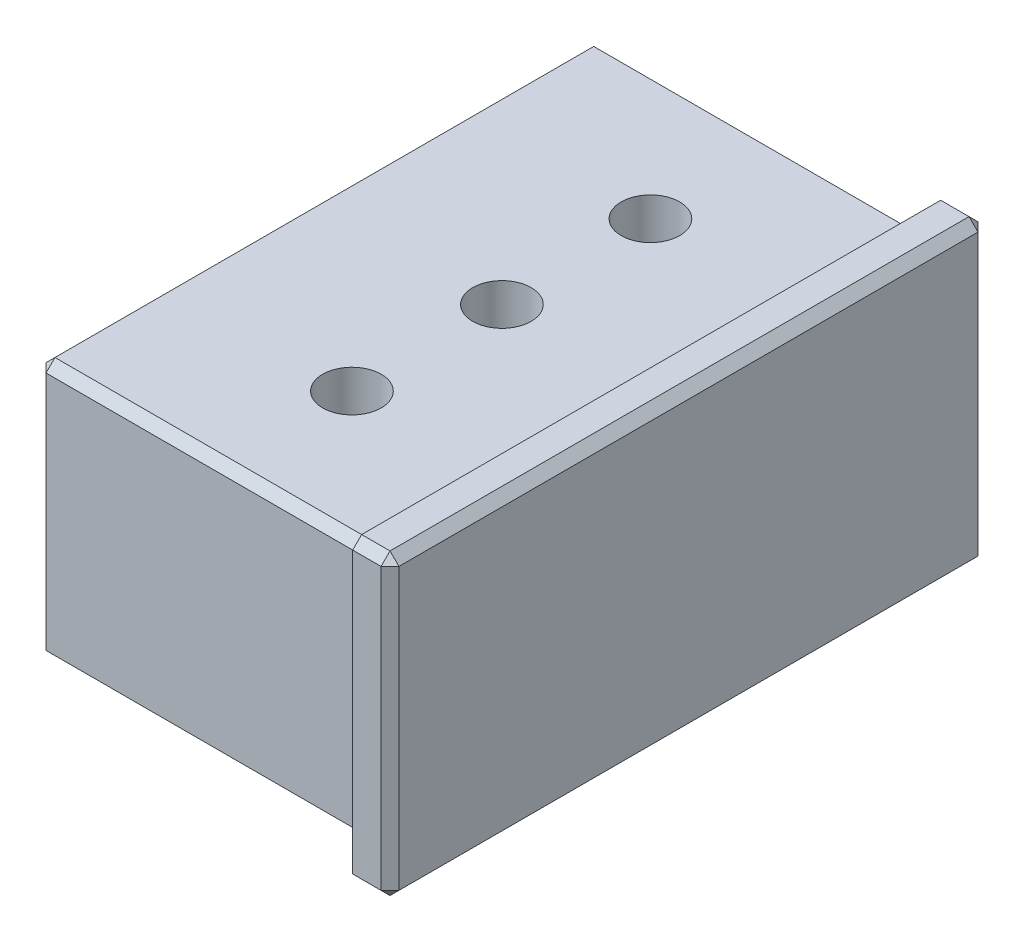
SolidWorks part; units mm, degrees
material "PET"
ref_plane "Front Plane" through (0, 0, 0) normal (0, 0, 1) x (1, 0, 0)
ref_plane "Top Plane" through (0, 0, 0) normal (0, 1, 0) x (1, 0, 0)
ref_plane "Right Plane" through (0, 0, 0) normal (1, 0, 0) x (0, 0, -1)
sketch "Sketch1" plane through (0, 0, 0) normal (1, 0, 0) x (0, 0, -1)
  line L1 (0, 0) -> (47.371, 0)
  line L2 (0, 0) -> (0, 21.971)
  line L3 (0, 21.971) -> (47.371, 21.971)
  line L4 (47.371, 0) -> (47.371, 21.971)
  dimension "D1" = 21.971
  dimension "D2" = 47.371
extrude "Boss-Extrude1" add sketch "Sketch1" along normal blind 28.575
sketch "Sketch2" plane through (28.575, 0, 0) normal (1, 0, 0) x (0, 0, -1)
  line L0 (0, 21.971) -> (47.371, 0) construction
  line L1 (0, 0) -> (47.371, 21.971) construction
  line L9 (49.0855, -1.7145) -> (-1.7145, -1.7145)
  line L10 (49.0855, -1.7145) -> (49.0855, 23.6855)
  line L11 (49.0855, 23.6855) -> (-1.7145, 23.6855)
  line L12 (-1.7145, -1.7145) -> (-1.7145, 23.6855)
  line L13 (49.0855, -1.7145) -> (-1.7145, 23.6855) construction
  line L14 (49.0855, 23.6855) -> (-1.7145, -1.7145) construction
  point P0 (23.6855, 10.9855)
  dimension "D1" = 50.8
  dimension "D2" = 25.4
extrude "Boss-Extrude2" add sketch "Sketch2" along normal blind 3.175
chamfer "Chamfer1" distance 0.762 angle 45 16 edges at (31.75, 23.6855, -23.6855) (30.1625, 23.6855, -49.0855) (31.75, 10.9855, -49.0855) (30.1625, -1.7145, -49.0855) (31.75, -1.7145, -23.6855) (30.1625, -1.7145, 1.7145) (31.75, 10.9855, 1.7145) (30.1625, 23.6855, 1.7145) (0, 0, -23.6855) (14.2875, 0, -47.371) (0, 10.9855, -47.371) (14.2875, 21.971, -47.371) (0, 21.971, -23.6855) (14.2875, 21.971, 0) (0, 10.9855, 0) (14.2875, 0, 0)
sketch "Sketch3" plane through (0, 21.971, 0) normal (0, 1, 0) x (1, 0, 0)
  circle A0 centre (15.875, 23.6855) radius 2.4892
  circle A1 centre (15.875, 36.322) radius 2.4892
  circle A2 centre (15.875, 10.922) radius 2.4892
  dimension "D1" = 4.9784
extrude "Cut-Extrude1" cut sketch "Sketch3" against normal through all
equation "\"D1@Sketch1\"=1-2*0.065-0.005"
equation "\"D2@Sketch1\"=2-2*0.065-0.005"
